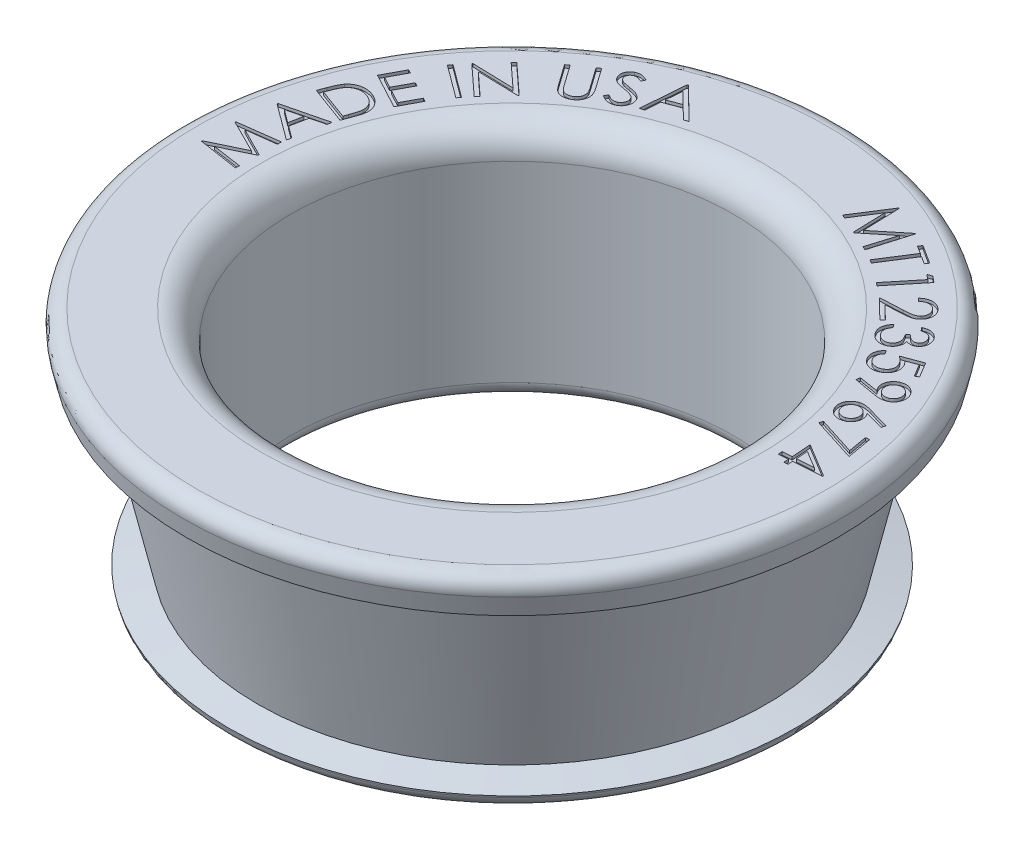
SolidWorks part; units mm, degrees
ref_plane "Front Plane" through (0, 0, 0) normal (0, 0, 1) x (1, 0, 0)
ref_plane "Top Plane" through (0, 0, 0) normal (0, 1, 0) x (1, 0, 0)
ref_plane "Right Plane" through (0, 0, 0) normal (1, 0, 0) x (0, 0, -1)
sketch "Sketch1" plane through (0, 0, 0) normal (0, 0, 1) x (1, 0, 0)
  line L0 (0, 12.1895) -> (0, 0) construction
  line L1 (0, 0) -> (-20.3595, 0) construction
  line L2 (-15, 1) -> (-15, 14)
  line L3 (-17, 16) -> (-21.35, 16)
  line L4 (-22.3256, 14.7805) -> (-22.0353, 13.49)
  line L5 (-22.0353, 13.49) -> (-20.084, 13.929)
  line L6 (-20.084, 13.929) -> (-17.2514, 1.339)
  line L7 (-17.2514, 1.339) -> (-19.2026, 0.9)
  line L8 (-19.2026, 0.9) -> (-19.1757, 0.7805)
  line L9 (-18.2001, 0) -> (-16, 0)
  arc A0 (-15, 14) -> (-17, 16) centre (-17, 14) ccw
  arc A1 (-15, 1) -> (-16, 0) centre (-16, 1) cw
  arc A2 (-19.1757, 0.7805) -> (-18.2001, 0) centre (-18.2001, 1) ccw
  arc A3 (-21.35, 16) -> (-22.3256, 14.7805) centre (-21.35, 15) ccw
  point P6 (0, 0)
  point P15 (-15, 16)
  point P18 (-15, 0)
  point P21 (-19.0001, 0)
  point P24 (-22.6, 16)
  dimension "D8" = 2
  dimension "D9" = 1
  dimension "D1" = 15
  dimension "D2" = 16
  dimension "D3" = 0.9
  dimension "D4" = 7.6
  dimension "D5" = 2
  dimension "D6" = 77.32
  dimension "D7" = 2.51
revolve "Revolve1" add sketch "Sketch1" angle 360 about L0
sketch "Sketch2" plane through (0, 16, 0) normal (0, 1, 0) x (1, 0, 0)
  circle A0 centre (0, 0) radius 17.64 construction
  text T0 "MADE IN USA          MT12359674" font "Century Gothic" height 2.75
  dimension "D1" = 35.28
extrude "Cut-Extrude1" cut sketch "Sketch2" against normal blind 0.2
